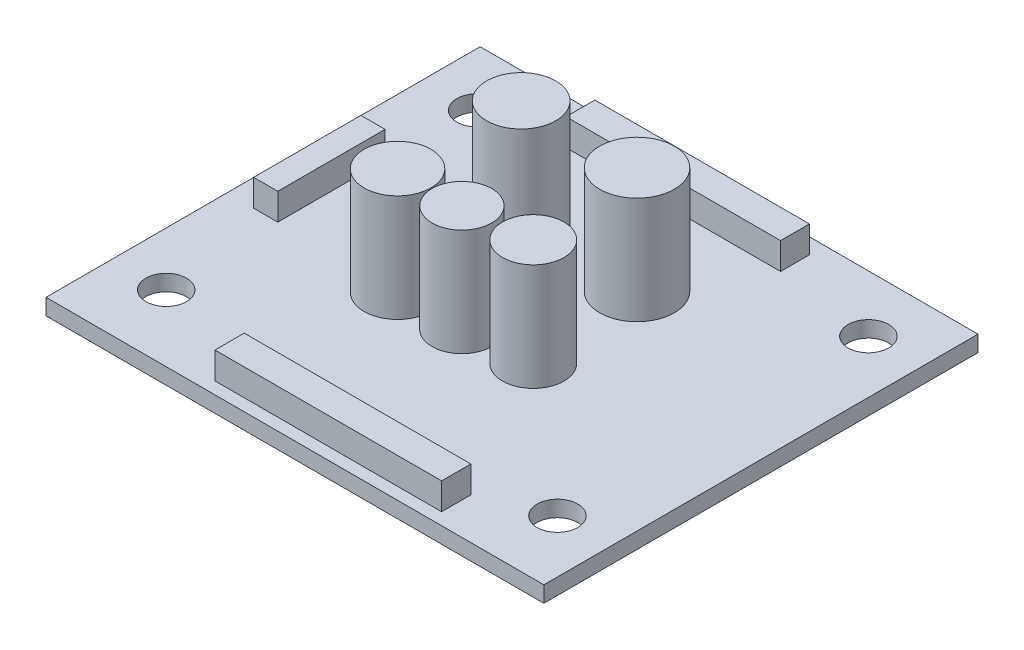
SolidWorks part; units mm, degrees
ref_plane "Front Plane" through (0, 0, 0) normal (0, 0, 1) x (1, 0, 0)
ref_plane "Top Plane" through (0, 0, 0) normal (0, 1, 0) x (1, 0, 0)
ref_plane "Right Plane" through (0, 0, 0) normal (1, 0, 0) x (0, 0, -1)
sketch "Sketch1" plane through (0, 0, 0) normal (0, 1, 0) x (1, 0, 0)
  line L1 (-4.0085, 27.4702) -> (33.1997, 27.4702)
  line L2 (-4.0085, 27.4702) -> (-4.0085, -4.9735)
  line L3 (-4.0085, -4.9735) -> (33.1997, -4.9735)
  line L4 (33.1997, 27.4702) -> (33.1997, -4.9735)
  circle A0 centre (0, 0) radius 1.52
  circle A1 centre (29.24, 0) radius 1.52
  circle A2 centre (29.24, 23.24) radius 1.52
  circle A3 centre (0, 23.24) radius 1.52
  dimension "D1" = 3.04
  dimension "D2" = 2
  dimension "D3" = 2
extrude "Boss-Extrude1" add sketch "Sketch1" along normal blind 1.2
sketch "Sketch2" plane through (0, 1.2, 0) normal (0, 1, 0) x (1, 0, 0)
  circle A0 centre (9.0281, 17.5009) radius 2.5831
  circle A1 centre (17.6854, 17.5009) radius 2.7901
  circle A2 centre (8.7949, 8.4938) radius 2.5
  circle A3 centre (18.4724, 8.9601) radius 2.2974
  circle A4 centre (13.6045, 8.4938) radius 2.2295
  dimension "D1" = 5
extrude "Boss-Extrude3" add sketch "Sketch2" along normal blind 8
sketch "Sketch3" plane through (0, 1.2, 0) normal (0, 1, 0) x (1, 0, 0)
  line L1 (7.7164, -1.8834) -> (24.6521, -1.8834)
  line L2 (7.7164, -1.8834) -> (7.7164, -4.0696)
  line L3 (7.7164, -4.0696) -> (24.6521, -4.0696)
  line L4 (24.6521, -1.8834) -> (24.6521, -4.0696)
  line L5 (5.7342, 26.304) -> (21.7663, 26.304)
  line L6 (5.7342, 26.304) -> (5.7342, 24.1469)
  line L7 (5.7342, 24.1469) -> (21.7663, 24.1469)
  line L8 (21.7663, 26.304) -> (21.7663, 24.1469)
  line L9 (-2.0195, 16.5681) -> (-0.2122, 16.5681)
  line L10 (-2.0195, 16.5681) -> (-2.0195, 8.5521)
  line L11 (-2.0195, 8.5521) -> (-0.2122, 8.5521)
  line L12 (-0.2122, 16.5681) -> (-0.2122, 8.5521)
extrude "Boss-Extrude4" add sketch "Sketch3" along normal blind 2
